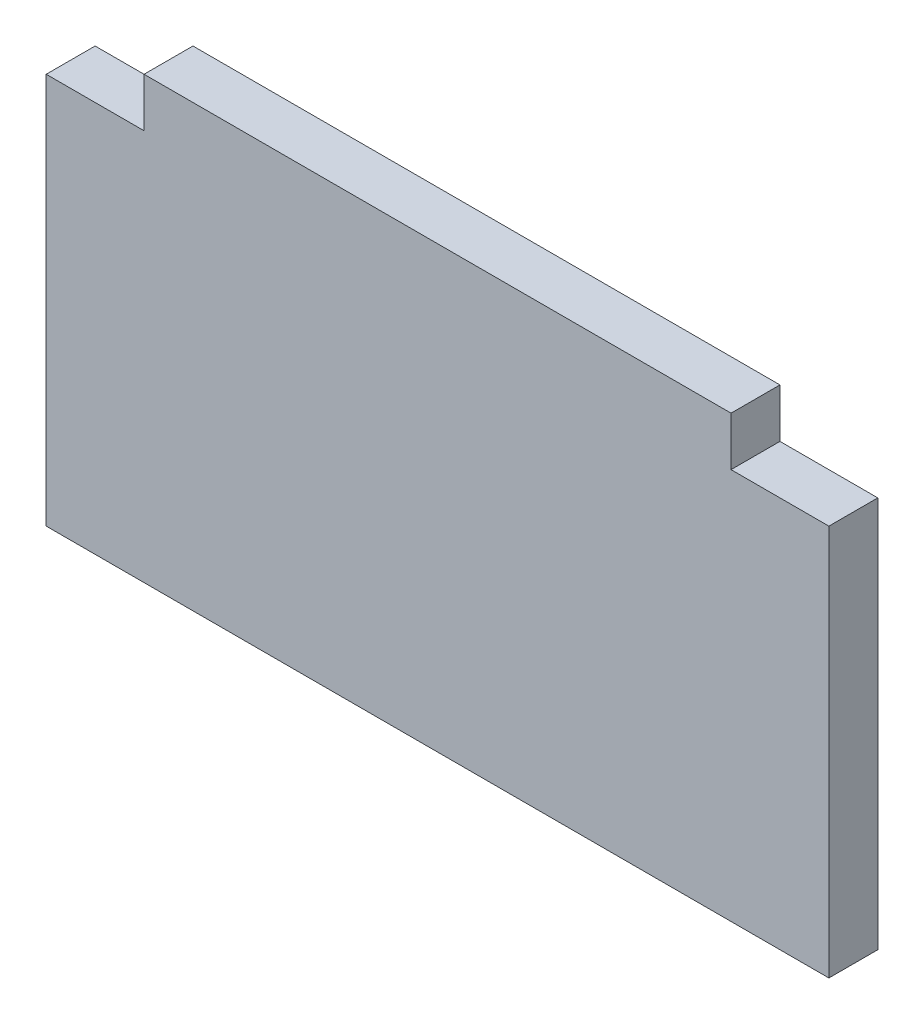
SolidWorks part; units mm, degrees
material "Acrylic (Medium-high impact)"
ref_plane "Front Plane" through (0, 0, 0) normal (0, 0, 1) x (1, 0, 0)
ref_plane "Top Plane" through (0, 0, 0) normal (0, 1, 0) x (1, 0, 0)
ref_plane "Right Plane" through (0, 0, 0) normal (1, 0, 0) x (0, 0, -1)
sketch "Sketch1" plane through (0, 0, 0) normal (0, 0, 1) x (1, 0, 0)
  line L1 (-50.8, 28.575) -> (50.8, 28.575)
  line L2 (-50.8, 28.575) -> (-50.8, -28.575)
  line L3 (-50.8, -28.575) -> (50.8, -28.575)
  line L4 (50.8, 28.575) -> (50.8, -28.575)
  line L5 (-50.8, 28.575) -> (50.8, -28.575) construction
  line L6 (-50.8, -28.575) -> (50.8, 28.575) construction
  point P0 (0, 0)
  dimension "D1" = 57.15
  dimension "D2" = 101.6
extrude "Boss-Extrude1" add sketch "Sketch1" along normal mid plane 6.35
sketch "Sketch2" plane through (0, 0, 3.175) normal (0, 0, 1) x (1, 0, 0)
  line L1 (-50.8, 28.575) -> (-38.1, 28.575)
  line L2 (-50.8, 28.575) -> (-50.8, 22.225)
  line L3 (-50.8, 22.225) -> (-38.1, 22.225)
  line L4 (-38.1, 28.575) -> (-38.1, 22.225)
  dimension "D1" = 6.35
  dimension "D2" = 12.7
extrude "Cut-Extrude1" cut sketch "Sketch2" against normal through all
mirror "Mirror1" about plane through (0, 0, 0) normal (1, 0, 0) of "Cut-Extrude1"
sketch "Sketch3" [suppressed] plane through (0, 0, 3.175) normal (0, 0, 1) x (1, 0, 0)
  line L0 (0, 0) -> (25.4, 0) construction
  circle A1 centre (25.4, 0) radius 3.175
  dimension "D1" = 25.4
  dimension "D2" = 6.35
extrude "Cut-Extrude2" [suppressed] cut sketch "Sketch3" against normal blind 6.35
equation "\"box_width\" = 7in"
equation "\"box_other_width\" = 6in"
equation "\"box_height\" = 2.25in"
equation "\"D1@Sketch1\"=\"box_height\""
equation "\"D2@Sketch1\"=\"side_length\""
equation "\"side_length\"= \"box_other_width\" - 2in"
